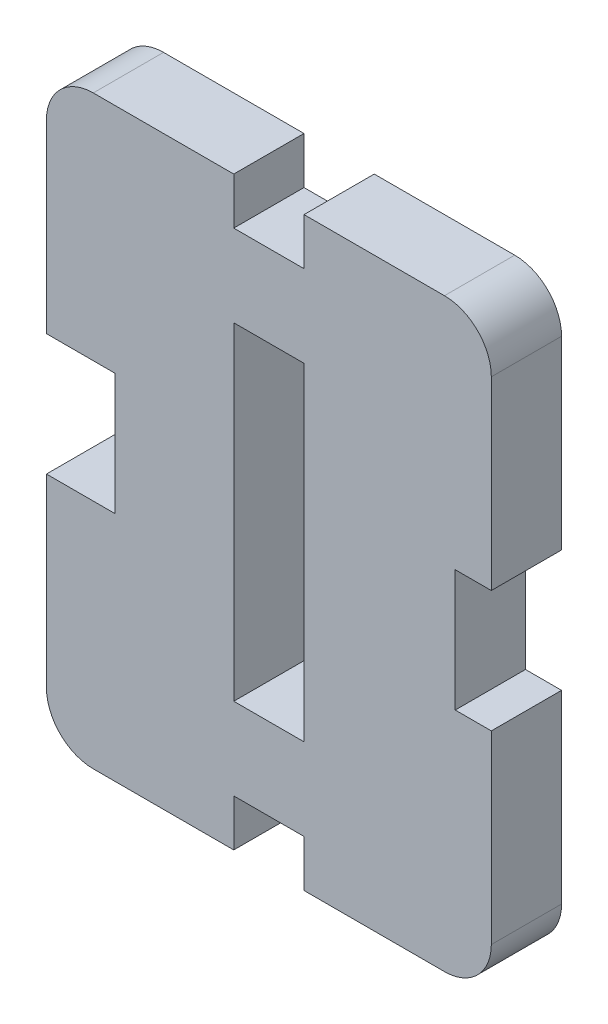
SolidWorks part; units mm, degrees
ref_plane "Front" through (0, 0, 0) normal (0, 0, 1) x (1, 0, 0)
ref_plane "Top" through (0, 0, 0) normal (0, 1, 0) x (1, 0, 0)
ref_plane "Right" through (0, 0, 0) normal (1, 0, 0) x (0, 0, -1)
sketch "Sketch1" plane through (0, 0, 0) normal (0, 0, 1) x (1, 0, 0)
  line L0 (-1044.1169, 50.4977) -> (-1044.1169, 36.4977)
  line L1 (-1049.1904, 43.4977) -> (-1034.6577, 43.4977) construction
  line L2 (-1041.1169, 36.4977) -> (-1041.1169, 50.4977)
  line L3 (-1041.1169, 50.4977) -> (-1044.1169, 50.4977)
  line L4 (-1033.1169, 53.9977) -> (-1033.1169, 46.0931)
  line L5 (-1033.1169, 46.0931) -> (-1034.6577, 46.0931)
  line L6 (-1034.6577, 46.0931) -> (-1034.6577, 40.9024)
  line L7 (-1050.1169, 30.9977) -> (-1044.1169, 30.9977)
  line L8 (-1042.6169, 53.9977) -> (-1041.1169, 53.9977)
  line L9 (-1041.1169, 53.9977) -> (-1041.1169, 55.9977)
  line L10 (-1041.1169, 55.9977) -> (-1035.1169, 55.9977)
  line L11 (-1042.6169, 53.9977) -> (-1044.1169, 53.9977)
  line L12 (-1044.1169, 53.9977) -> (-1044.1169, 55.9977)
  line L13 (-1052.1169, 40.9024) -> (-1052.1169, 32.9977)
  line L14 (-1049.1904, 40.9024) -> (-1052.1169, 40.9024)
  line L15 (-1044.1169, 32.9977) -> (-1044.1169, 30.9977)
  line L16 (-1042.6169, 32.9977) -> (-1044.1169, 32.9977)
  line L17 (-1041.1169, 30.9977) -> (-1035.1169, 30.9977)
  line L18 (-1049.1904, 40.9024) -> (-1049.1904, 46.0931)
  line L19 (-1049.1904, 46.0931) -> (-1052.1169, 46.0931)
  line L20 (-1052.1169, 46.0931) -> (-1052.1169, 53.9977)
  line L21 (-1041.1169, 32.9977) -> (-1041.1169, 30.9977)
  line L22 (-1042.6169, 32.9977) -> (-1041.1169, 32.9977)
  line L23 (-1033.1169, 40.9024) -> (-1034.6577, 40.9024)
  line L24 (-1050.1169, 55.9977) -> (-1044.1169, 55.9977)
  line L25 (-1033.1169, 32.9977) -> (-1033.1169, 40.9024)
  line L26 (-1041.1169, 36.4977) -> (-1044.1169, 36.4977)
  arc A0 (-1052.1169, 53.9977) -> (-1050.1169, 55.9977) centre (-1050.1169, 53.9977) cw
  arc A1 (-1033.1169, 53.9977) -> (-1035.1169, 55.9977) centre (-1035.1169, 53.9977) ccw
  arc A2 (-1033.1169, 32.9977) -> (-1035.1169, 30.9977) centre (-1035.1169, 32.9977) cw
  arc A3 (-1052.1169, 32.9977) -> (-1050.1169, 30.9977) centre (-1050.1169, 32.9977) ccw
  point P8 (-1044.1169, 43.4977)
  point P38 (-1041.1169, 43.4977)
  dimension "D1" = 2
  dimension "D2" = 3
  dimension "D3" = 8
  dimension "D4" = 8
  dimension "D5" = 14
  dimension "D6" = 2
  dimension "D7" = 25
extrude "Base-Extrude" add sketch "Sketch1" along normal blind 3
